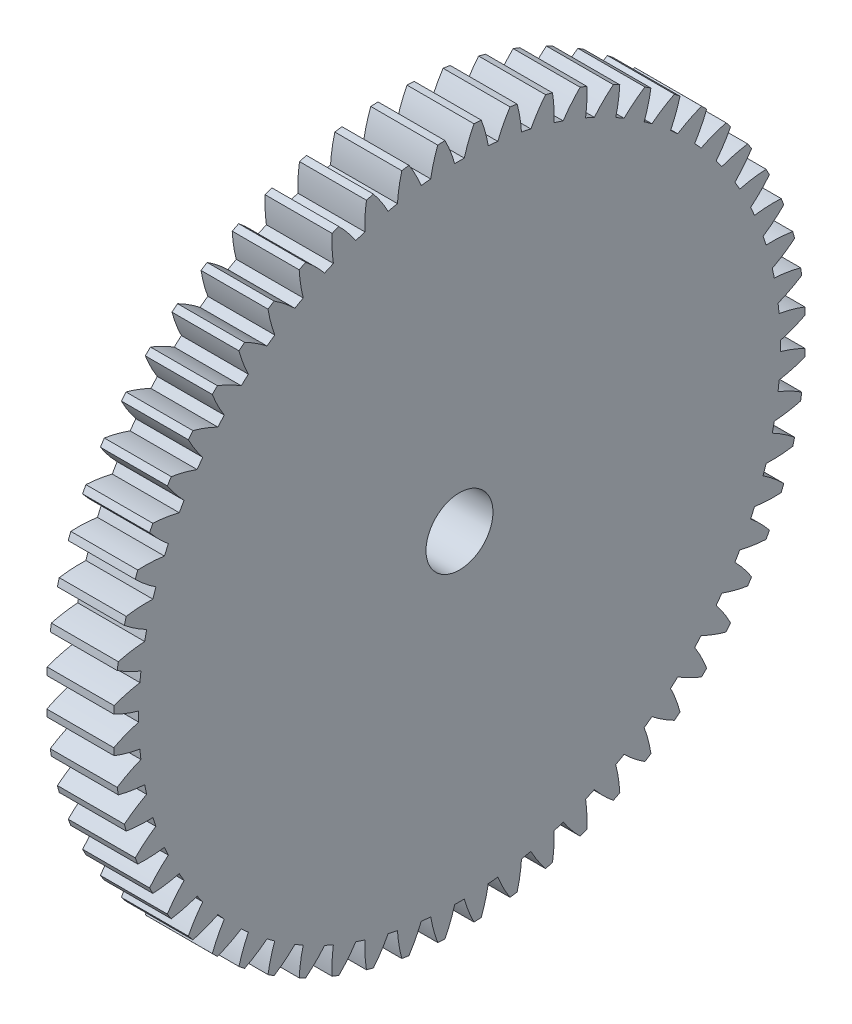
SolidWorks part; units mm, degrees
ref_plane "Plane1" through (0, 0, 0) normal (0, 0, 1) x (1, 0, 0)
ref_plane "Plane2" through (0, 0, 0) normal (0, 1, 0) x (1, 0, 0)
ref_plane "Plane3" through (0, 0, 0) normal (1, 0, 0) x (0, 0, -1)
sketch "HoldingSke" plane through (0, 0, 0) normal (0, 1, 0) x (1, 0, 0)
  line L0 (0, 0) -> (1, -1.7321)
  line L1 (-15, 0) -> (100, 0) construction
  line L2 (0, 0) -> (-2.1039, 2.3779)
  line L3 (0, 0) -> (-11.863, 4.5341)
  line L4 (0, 0) -> (4.318, 7.479)
  line L5 (0, 0) -> (-46.8476, -17.4728)
  line L6 (0, 0) -> (-2.4869, -1.6779)
  line L7 (-2.1039, 2.3779) -> (8.6586, 51.2059)
  line L8 (-76.2, 54.61) -> (-75.7, 54.61)
  line L9 (-71.009, 38.7566) -> (-53.1078, 45.2721)
  line L10 (-76.2, 71.12) -> (104.1128, 71.12)
  line L11 (0, 0) -> (-3, 0)
  line L12 (-76.2, 101.6) -> (-76.181, 101.6)
  line L13 (24.9733, 27.94) -> (52.9518, 28.4284)
  line L14 (24.9733, 27.94) -> (24.9743, 27.94)
  line L15 (24.9733, 27.94) -> (100.4006, 29.5858)
  line L16 (-63.627, -0.5) -> (-12.827, -0.5)
  circle A0 centre (0, 0) radius 1.5
  circle A1 centre (0, 0) radius 14.374
  circle A2 centre (0, 0) radius 37.5
  circle A3 centre (0, 0) radius 1.5
  dimension "MHD" = 28.748
  dimension "Hub_dia" = 75
  dimension "Num_teeth" = 60
  dimension "Pitch" = 2
  dimension "Overall_len" = 50
  dimension "Show_teeth" = 60
  dimension "Thickness" = 3
  dimension "OAL" = 50.0001
  dimension "Ap" = 20
  dimension "H" = 19.05
  dimension "Pitch_radius" = 180.3128
  dimension "Width" = 3
  dimension "Backlash" = 0.019
  dimension "Addendum_fac" = 1
  dimension "Dedendum_fac" = 1.25
  dimension "Clearance_fac" = 0.25
  dimension "Dedendum_add" = 0.001
  dimension "Module" = 0.5
sketch "BasProSke" plane through (0, 0, 0) normal (0, 1, 0) x (1, 0, 0)
  line L0 (-10, 0) -> (60, 0) construction
  line L1 (0, 0) -> (0, 15.5)
  line L2 (0, 0) -> (3, 0)
  line L3 (3, 0) -> (3, 15.5)
  line L4 (3, 15.5) -> (0, 15.5)
  dimension "Thickness" = 3
  dimension "Diameter" = 31
revolve "Base-Revolve" add sketch "BasProSke" angle 360 about L0
sketch "TooCutSke" plane through (0, 0, 0) normal (1, 0, 0) x (0, 0, -1)
  line L1 (0, 0) -> (0, 107) construction
  line L2 (0, 0) -> (-0.4259, 14.994) construction
  line L3 (0, 0) -> (-1.5696, 29.9503) construction
  line L4 (-0.4259, 14.994) -> (-0.7848, 14.9751) construction
  arc A0 (0.2149, 14.3724) -> (-0.2149, 14.3724) centre (0, 0) ccw
  arc A1 (0.6627, 15.5112) -> (-0.6627, 15.5112) centre (0, 0) ccw
  circle A2 centre (0, 0) radius 15 construction
  circle A3 centre (0, 0) radius 14.0954 construction
  arc A4 (-0.2149, 14.3724) -> (-0.6627, 15.5112) centre (-5.9936, 12.7576) ccw
  arc A5 (0.6627, 15.5112) -> (0.2149, 14.3724) centre (5.9936, 12.7576) ccw
  dimension "Root_dia" = 28.748
  dimension "Overcut_dia" = 31.0508
  dimension "Pitch_dia" = 30
  dimension "Base_dia" = 28.1908
  dimension "Flank_rad" = 6
  dimension "Half_ang" = 3
  dimension "Half_CT" = 0.3594
extrude "ToothCut" cut sketch "TooCutSke" along normal through all
fillet "Breaks" [suppressed] radius 0.01
fillet "RootFillets" [suppressed] radius 0.126
pattern_circular "TeethCuts" count 60 every 6 about axis through (-10, 0, 0) along (1, 0, 0) of "ToothCut", "RootFillets", "Breaks"
sketch "HubNeaOneSke" plane through (0, 0, 0) normal (-1, 0, 0) x (0, 0, 1)
  circle A0 centre (0, 0) radius 14.374
  dimension "Diameter" = 28.748
extrude "HubNearOne" [suppressed] add sketch "HubNeaOneSke" along normal blind 47.0001
sketch "HubNeaBotSke" plane through (0, 0, 0) normal (-1, 0, 0) x (0, 0, 1)
  circle A0 centre (0, 0) radius 14.374
  dimension "Diameter" = 28.748
extrude "HubNearBoth" [suppressed] add sketch "HubNeaBotSke" along normal blind 23.5
ref_plane "FarPln" through (3, 0, 0) normal (1, 0, 0) x (0, 0, -1)
sketch "HubFarSke" plane through (3, 0, 0) normal (1, 0, 0) x (0, 0, -1)
  circle A0 centre (0, 0) radius 14.374
  dimension "Diameter" = 28.748
extrude "HubFar" [suppressed] add sketch "HubFarSke" along normal blind 23.5
sketch "BorSke" plane through (0, 0, 0) normal (1, 0, 0) x (0, 0, -1)
  circle A0 centre (0, 0) radius 1.5
extrude "Bore" cut sketch "BorSke" along normal mid plane 100.0001
sketch "KeySke" plane through (0, 0, 0) normal (1, 0, 0) x (0, 0, -1)
  line L0 (-0.6, 0) -> (-0.6, 2)
  line L1 (-0.6, 2) -> (0.6, 2)
  line L2 (0.6, 2) -> (0.6, 0)
  line L3 (0, 0) -> (0, 34) construction
  line L4 (-0.6, 0) -> (0.6, 0)
extrude "Keyway" [suppressed] cut sketch "KeySke" along normal mid plane 100.0001
pattern_circular "Keyway2" [suppressed] count 2 every 90 about axis through (-10, 0, 0) along (1, 0, 0)
equation "' \"Module@HoldingSke\" = 6.35"
equation "' \"Num_teeth@HoldingSke\" = 12"
equation "' \"Ap@HoldingSke\" =  20"
equation "' \"Ap@HoldingSke\" = 20"
equation "' \"Width@HoldingSke\" = 0.5 * 25.4"
equation "' \"Hub_dia@HoldingSke\"= 1 * 25.4"
equation "' \"Hub_dia@HoldingSke\" = 1 * 25.4"
equation "' \"Overall_len@HoldingSke\" = 1.0 * 25.4"
equation "' \"Bore@HoldingSke\" = 0.75 * 25.4"
equation "' \"T_dim@HoldingSke\" = 0.1 * 25.4"
equation "' \"Width@KeySke\" = 0.25 * 25.4"
equation "' \"Show_teeth@HoldingSke\" = 13"
equation "' \"Backlash@HoldingSke\" = 0.009 * 25.4"
equation "' \"Addendum_fac@HoldingSke\" = 1.0"
equation "' \"Dedendum_fac@HoldingSke\" = 1.25"
equation "' \"Dedendum_add@HoldingSke\" = 0.00005 * 25.4"
equation "' \"Clearance_fac@HoldingSke\" = 0.25"
equation "\"Pitch@HoldingSke\" = 1 / \"Module@HoldingSke\""
equation "\"Overcut_dia@TooCutSke\" = (\"Num_teeth@HoldingSke\" + 2 * \"Addendum_fac@HoldingSke\") / \"Pitch@HoldingSke\" + 0.002 * 25.4"
equation "\"Pitch_dia@TooCutSke\" = \"Num_teeth@HoldingSke\" / \"Pitch@HoldingSke\""
equation "\"Base_dia@TooCutSke\" = \"Num_teeth@HoldingSke\" / \"Pitch@HoldingSke\" * cos((\"Ap@HoldingSke\"  * 3.14159265 / 180))"
equation "\"Root_dia@TooCutSke\" = (\"Num_teeth@HoldingSke\" + 2) / \"Pitch@HoldingSke\" - 2 * (\"Addendum_fac@HoldingSke\" + \"Dedendum_fac@HoldingSke\") / \"Pitch@HoldingSke\" - \"Dedendum_add@HoldingSke\" * 2"
equation "\"Half_ang@TooCutSke\" = 180 / \"Num_teeth@HoldingSke\""
equation "\"Half_CT@TooCutSke\" = \"Num_teeth@HoldingSke\" / \"Pitch@HoldingSke\" * sin((3.14159265 / 2 / \"Num_teeth@HoldingSke\")) / 2 - 7 * \"Backlash@HoldingSke\" / 4"
equation "\"Flank_rad@TooCutSke\" = \"Num_teeth@HoldingSke\" / \"Pitch@HoldingSke\" / 5"
equation "\"Radius@RootFillets\" = \"Clearance_fac@HoldingSke\" / \"Pitch@HoldingSke\" + \"Dedendum_add@HoldingSke\""
equation "\"Break_rad@Breaks\" = 0.02 / \"Pitch@HoldingSke\""
equation "\"Thickness@HoldingSke\" = \"Width@HoldingSke\""
equation "\"OAL@HoldingSke\" = \"Thickness@HoldingSke\""
equation "\"MHD@HoldingSke\" = (\"Num_teeth@HoldingSke\" + 2) / \"Pitch@HoldingSke\" - 2 * (\"Addendum_fac@HoldingSke\" + \"Dedendum_fac@HoldingSke\")  / \"Pitch@HoldingSke\" - \"Dedendum_add@HoldingSke\" * 2"
equation "\"MBD@HoldingSke\" = (\"Num_teeth@HoldingSke\" + 2) / \"Pitch@HoldingSke\" - 2 * (\"Addendum_fac@HoldingSke\" + \"Dedendum_fac@HoldingSke\")  / \"Pitch@HoldingSke\" - \"Dedendum_add@HoldingSke\" * 2 - 0.002 * 25.4"
equation "\"MHD@HoldingSke\" = ((sgn( \"MHD@HoldingSke\" - \"Hub_dia@HoldingSke\" )-1)*( \"MHD@HoldingSke\" - \"Hub_dia@HoldingSke\" ))/-2+ \"Hub_dia@HoldingSke\""
equation "\"MBD@HoldingSke\" = ((sgn( \"MBD@HoldingSke\" - \"Bore@HoldingSke\" )-1)*( \"MBD@HoldingSke\" - \"Bore@HoldingSke\" ))/-2+ \"Bore@HoldingSke\""
equation "\"OAL@HoldingSke\" = ((sgn( \"OAL@HoldingSke\" - \"Overall_len@HoldingSke\" )+1)*( \"OAL@HoldingSke\" - \"Overall_len@HoldingSke\" ))/2 + \"Overall_len@HoldingSke\" + 0.000002 * 25.4"
equation "\"Num_teeth@TeethCuts\" = int( \"Show_teeth@HoldingSke\" ) + 1"
equation "\"Num_teeth@TeethCuts\" = ((sgn( \"Num_teeth@TeethCuts\" - \"Num_teeth@HoldingSke\" )-1)*( \"Num_teeth@TeethCuts\" - \"Num_teeth@HoldingSke\" ))/-2+ \"Num_teeth@HoldingSke\""
equation "\"Num_teeth@TeethCuts\" = ((sgn( \"Num_teeth@TeethCuts\" - 2.0)+1)*( \"Num_teeth@TeethCuts\" - 2.0))/2 +2.0"
equation "\"Angle@TeethCuts\" = 360.0 / \"Num_teeth@HoldingSke\""
equation "\"Diameter@BasProSke\" = (\"Num_teeth@HoldingSke\" + 2 * \"Addendum_fac@HoldingSke\") / \"Pitch@HoldingSke\""
equation "\"Thickness@BasProSke\"  = \"Thickness@HoldingSke\""
equation "' \"Fillet_rad@BasProSke\" =  \"Thickness@HoldingSke\" * 0.05"
equation "' \"Fillet_rad@BasProSke\" = \"Thickness@HoldingSke\" * 0.05"
equation "\"MHD@HoldingSke\" = ((sgn( \"MHD@HoldingSke\" - \"Root_dia@TooCutSke\" )-1)*( \"MHD@HoldingSke\" - \"Root_dia@TooCutSke\" ))/-2+ \"Root_dia@TooCutSke\""
equation "\"Diameter@HubNeaOneSke\" = \"MHD@HoldingSke\""
equation "\"Length@HubNearOne\" = \"OAL@HoldingSke\" - \"Thickness@BasProSke\""
equation "\"Diameter@HubNeaBotSke\" = \"MHD@HoldingSke\""
equation "\"Length@HubNearBoth\" = ( \"OAL@HoldingSke\" - \"Thickness@BasProSke\" ) / 2.0"
equation "\"Thickness@FarPln\" = \"Thickness@BasProSke\""
equation "\"Diameter@HubFarSke\" = \"MHD@HoldingSke\""
equation "\"Length@HubFar\" = ( \"OAL@HoldingSke\" - \"Thickness@BasProSke\" ) / 2.0"
equation "\"Diameter@BorSke\" = \"MBD@HoldingSke\""
equation "\"D1@Bore\" = \"OAL@HoldingSke\" * 2.0"
equation "\"D1@Keyway\" = \"OAL@HoldingSke\" * 2.0"
equation "\"Offset@KeySke\" = \"T_dim@HoldingSke\" + \"MBD@HoldingSke\" / 2.0"
